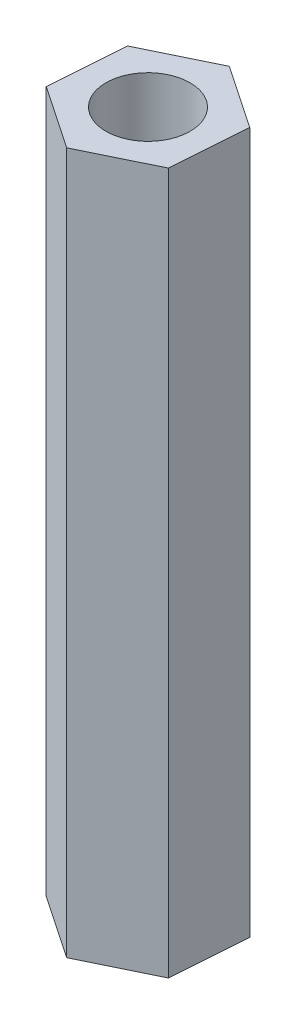
SolidWorks part; units mm, degrees
material "黄铜"
ref_plane "前视基准面" through (0, 0, 0) normal (0, 0, 1) x (1, 0, 0)
ref_plane "上视基准面" through (0, 0, 0) normal (0, 1, 0) x (1, 0, 0)
ref_plane "右视基准面" through (0, 0, 0) normal (1, 0, 0) x (0, 0, -1)
sketch "草图1" plane through (0, 0, 0) normal (0, 1, 0) x (1, 0, 0)
  line L1 (2.4405, 1.1863) -> (0.1928, 2.7067)
  line L2 (0.1928, 2.7067) -> (-2.2476, 1.5203)
  line L3 (-2.2476, 1.5203) -> (-2.4405, -1.1863)
  line L4 (-2.4405, -1.1863) -> (-0.1928, -2.7067)
  line L5 (-0.1928, -2.7067) -> (2.2476, -1.5203)
  line L6 (2.2476, -1.5203) -> (2.4405, 1.1863)
  circle A0 centre (0, 0) radius 2.35 construction
  point P1 (2.3441, -0.167)
  dimension "D1" = 4.7
  dimension "D2" = 5.4271
extrude "凸台-拉伸1" add sketch "草图1" along normal blind 25
sketch "草图2" plane through (0, 0, 0) normal (0, -1, 0) x (1, 0, 0)
  circle A0 centre (0, 0) radius 1.5
  dimension "D1" = 3
extrude "切除-拉伸1" cut sketch "草图2" against normal through all
